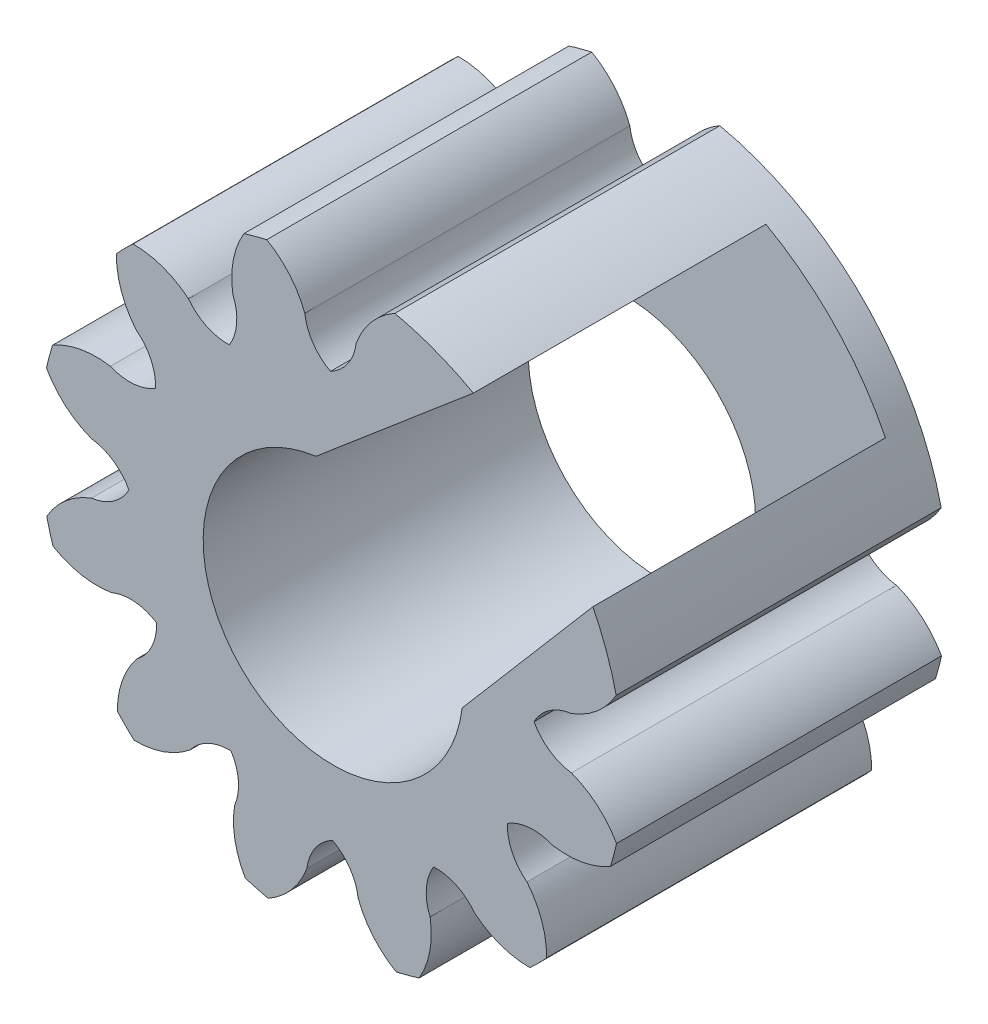
SolidWorks part; units mm, degrees
ref_plane "Front Plane" through (0, 0, 0) normal (0, 0, 1) x (1, 0, 0)
ref_plane "Top Plane" through (0, 0, 0) normal (0, 1, 0) x (1, 0, 0)
ref_plane "Right Plane" through (0, 0, 0) normal (1, 0, 0) x (0, 0, -1)
sketch "Sketch1" plane through (0, 0, 0) normal (0, 0, 1) x (1, 0, 0)
  circle A3 centre (0, 0) radius 8.9834
extrude "Boss-Extrude2" add sketch "Sketch1" against normal blind 10
sketch "Sketch2" plane through (0, 0, 0) normal (0, 0, 1) x (1, 0, 0)
  line L4 (-1.9748, 2.4771) -> (4.366, 7.8511)
  line L6 (2.911, -2.0089) -> (8.0441, 3.9993)
  arc A2 (-1.9748, 2.4771) -> (2.911, -2.0089) centre (0.051, -0.2202) ccw
  circle A3 centre (0, 0) radius 8.9834 construction
  arc A4 (4.366, 7.8511) -> (8.0441, 3.9993) centre (0, 0) cw
extrude "Cut-Extrude1" cut sketch "Sketch2" against normal blind 9
sketch "Sketch9" plane through (0, 0, 0) normal (0, 0, 1) x (1, 0, 0)
  circle A0 centre (0.051, -0.2202) radius 4
  dimension "D1" = 8
extrude "Cut-Extrude4" cut sketch "Sketch9" against normal blind 10
sketch "Sketch10" plane through (0, 0, 0) normal (0, 0, 1) x (1, 0, 0)
  line L0 (-0.0306, -5.0091) -> (-0.0306, 10.9587) construction
  arc A0 (-0.0306, 6.2325) -> (0.7594, 7.3825) centre (-0.7394, 7.5658) ccw
  arc A1 (0.7594, 7.3825) -> (2.0694, 8.8325) centre (3.2502, 6.449) cw
  arc A2 (-0.0306, 6.2325) -> (-0.8206, 7.3825) centre (0.6782, 7.5658) cw
  arc A3 (-0.8206, 7.3825) -> (-2.1306, 8.8325) centre (-3.3114, 6.449) ccw
  arc A4 (-2.1306, 8.8325) -> (2.0694, 8.8325) centre (-0.0306, -5.0091) cw
  dimension "D1" = 2.66
  dimension "D2" = 1.51
  dimension "D3" = 1.45
  dimension "D4" = 1.31
  dimension "D5" = 1.15
  dimension "D6" = 0.79
extrude "Cut-Extrude5" cut sketch "Sketch10" against normal blind 10
pattern_circular "CirPattern2" count 10 every 30 about axis through (0, 0, 0) along (0, 0, 1) of "Cut-Extrude5"
